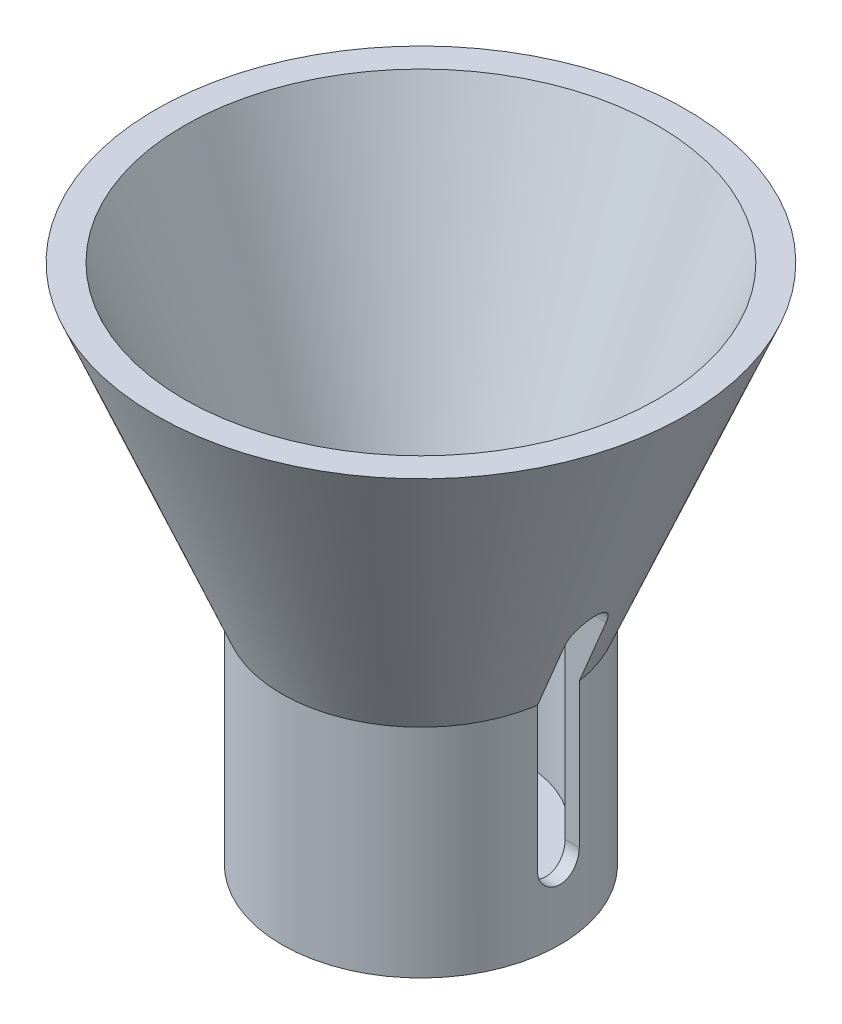
SolidWorks part; units mm, degrees
material "PE High Density"
ref_plane "Front Plane" through (0, 0, 0) normal (0, 0, 1) x (1, 0, 0)
ref_plane "Top Plane" through (0, 0, 0) normal (0, 1, 0) x (1, 0, 0)
ref_plane "Right Plane" through (0, 0, 0) normal (1, 0, 0) x (0, 0, -1)
sketch "Sketch2" plane through (0, 0, 0) normal (0, 0, 1) x (1, 0, 0)
  line L0 (0, 0) -> (0, -71048.4048) construction
  line L1 (0, 0) -> (-25.4, 0)
  line L2 (-25.4, 0) -> (-25.4, 39.6701)
  line L3 (-25.4, 39.6701) -> (-48.4219, 95.25)
  line L4 (-48.4219, 95.25) -> (-43.267, 95.25)
  line L5 (-43.267, 95.25) -> (-22.225, 44.45)
  line L7 (-19.05, 6.35) -> (0, 6.35)
  line L8 (0, 6.35) -> (0, 0)
  line L9 (-22.225, 44.45) -> (-19.05, 44.45)
  line L10 (-19.05, 44.45) -> (-19.05, 6.35)
  dimension "D1" = 3.175
  dimension "D2" = 19.05
  dimension "D3" = 38.1
  dimension "D4" = 6.35
  dimension "D5" = 4.7625
  dimension "D6" = 22.5
  dimension "D7" = 50.8
  dimension "D8" = 6.35
revolve "Revolve1" add sketch "Sketch2" angle 360 about L0
sketch "Sketch3" plane through (0, 0, 0) normal (1, 0, 0) x (0, 0, -1)
  line L0 (0, 13.335) -> (0, 19.685) construction
  line L1 (-3.81, 51.435) -> (-3.81, 13.335)
  line L2 (3.81, 51.435) -> (3.81, 13.335)
  line L3 (48.4219, 95.25) -> (-48.4219, 95.25) construction
  arc A0 (-3.81, 13.335) -> (3.81, 13.335) centre (0, 13.335) ccw
  arc A1 (3.81, 51.435) -> (-3.81, 51.435) centre (0, 51.435) ccw
  dimension "D1" = 7.62
  dimension "D2" = 43.815
  dimension "D3" = 38.1
extrude "Cut-Extrude1" cut sketch "Sketch3" along normal through all
sketch "Sketch4" plane through (0, 0, 0) normal (0, -1, 0) x (1, 0, 0)
  circle A0 centre (0, 0) radius 3.2639 construction
  dimension "D1" = 6.5278
hole_wizard "F (0.257) Diameter Hole1" positions "Sketch5" profile "Sketch7" hole size "F" standard "ANSI Inch" end condition through all
sketch "Sketch5" plane through (0, 0, 0) normal (0, -1, 0) x (-1, 0, 0)
  point P0 (0, 0)
sketch "Sketch7" plane through (0, 0, 0) normal (1, 0, 0) x (0, 0, -1)
  line L0 (0, 0) -> (0, 95.25)
  line L1 (0, 95.25) -> (3.2639, 95.25)
  line L2 (3.2639, 95.25) -> (3.2639, 0)
  line L5 (3.2639, 0) -> (0, 0)
  line L11 (0, -6.35) -> (0, 107.95) construction
  dimension "Thru Hole Dia." = 6.5278
  dimension "Thru Hole Depth" = 95.25
sketch "Sketch8" plane through (0, 44.45, 0) normal (0, 1, 0) x (1, 0, 0)
  line L0 (0, 0) -> (20.8065, 14.5688) construction
  line L1 (0, 0) -> (20.8065, -14.5688) construction
  line L2 (0, -52.3875) -> (0, 52.3875) construction
  line L3 (15.6048, 10.9266) -> (18.7258, 13.112)
  line L4 (15.6048, -10.9266) -> (18.7258, -13.112)
  arc A0 (15.6048, 10.9266) -> (15.6048, -10.9266) centre (0, 0) cw
  circle A1 centre (0, 0) radius 19.05 construction
  arc A2 (25.1126, 3.81) -> (25.1126, -3.81) centre (0, 0) ccw construction
  arc A4 (18.7258, 13.112) -> (18.7258, -13.112) centre (0, 0) cw
  dimension "D3" = 3.81
  dimension "D1" = 70
  dimension "D2" = 55
extrude "Cut-Extrude2" cut sketch "Sketch8" against normal mid plane 76.2
